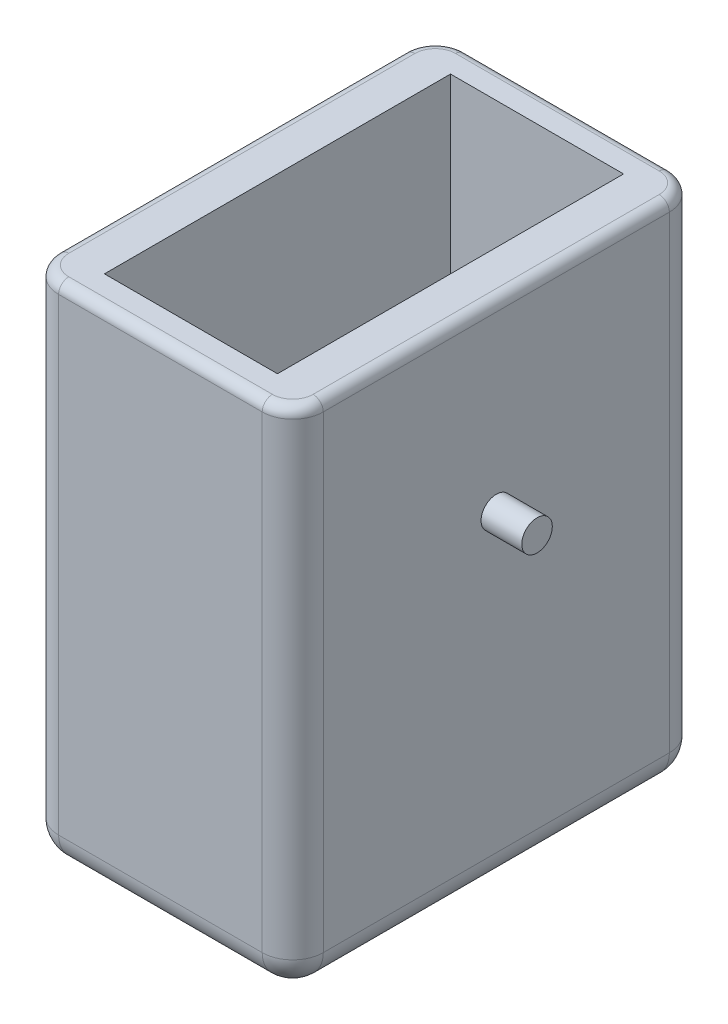
SolidWorks part; units mm, degrees
ref_plane "Alzado" through (0, 0, 0) normal (0, 0, 1) x (1, 0, 0)
ref_plane "Planta" through (0, 0, 0) normal (0, 1, 0) x (1, 0, 0)
ref_plane "Vista lateral" through (0, 0, 0) normal (1, 0, 0) x (0, 0, -1)
sketch "Croquis1" plane through (0, 0, 0) normal (0, 1, 0) x (1, 0, 0)
  line L1 (0, 0) -> (-26, 0)
  line L2 (0, 0) -> (0, 40)
  line L3 (0, 40) -> (-26, 40)
  line L4 (-26, 0) -> (-26, 40)
  dimension "D1" = 26
  dimension "D2" = 40
extrude "Saliente-Extruir1" add sketch "Croquis1" along normal blind 50
sketch "Croquis2" plane through (0, 50, 0) normal (0, 1, 0) x (1, 0, 0)
  line L0 (-26, 40) -> (-26, 0) construction
  line L1 (-21.5, 3) -> (-4.5, 3)
  line L2 (-21.5, 3) -> (-21.5, 37)
  line L3 (-21.5, 37) -> (-4.5, 37)
  line L4 (-4.5, 3) -> (-4.5, 37)
  line L5 (0, 0) -> (0, 40) construction
  line L6 (0, 40) -> (-26, 40) construction
  line L7 (-26, 0) -> (0, 0) construction
  dimension "D1" = 4.5
  dimension "D2" = 4.5
  dimension "D3" = 3
  dimension "D4" = 3
extrude "Cortar-Extruir1" cut sketch "Croquis2" against normal blind 47
fillet "Redondeo1" radius 3 8 edges at (-13, 0, -40) (-26, 0, -20) (-13, 0, 0) (0, 0, -20) (-26, 25, -40) (0, 25, -40) (0, 25, 0) (-26, 25, 0)
fillet "Redondeo2" radius 1 8 edges at (-25.1213, 50, -39.1213) (-13, 50, -40) (-0.8787, 50, -39.1213) (0, 50, -20) (-0.8787, 50, -0.8787) (-13, 50, 0) (-25.1213, 50, -0.8787) (-26, 50, -20)
sketch "Croquis4" plane through (-26, 0, 0) normal (-1, 0, 0) x (0, 0, 1)
  line L0 (-20, 3) -> (-20, 32) construction
  line L1 (-37, 3) -> (-3, 3) construction
  line L3 (-3, 49) -> (-37, 49) construction
  circle A0 centre (-20, 32) radius 1.5
  dimension "D1" = 3
  dimension "D2" = 17
extrude "Saliente-Extruir2" add sketch "Croquis4" along normal blind 4
sketch "Croquis5" plane through (0, 0, 0) normal (1, 0, 0) x (0, 0, -1)
  line L0 (20, 3) -> (20, 32) construction
  line L1 (3, 3) -> (37, 3) construction
  line L2 (37, 49) -> (3, 49) construction
  circle A0 centre (20, 32) radius 1.5
  dimension "D1" = 3
  dimension "D2" = 17
extrude "Saliente-Extruir3" add sketch "Croquis5" along normal blind 4
